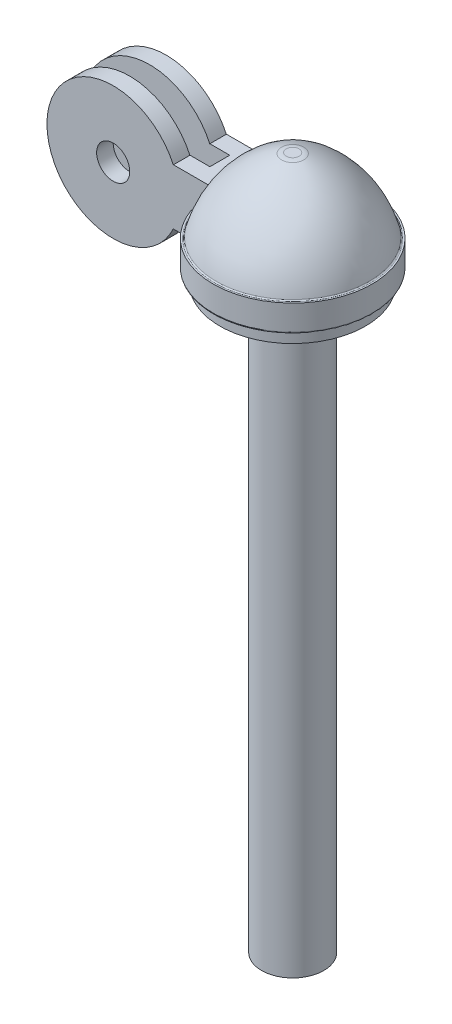
SolidWorks part; units mm, degrees
material "Chrome Stainless Steel"
ref_plane "Front" through (0, 0, 0) normal (0, 0, 1) x (1, 0, 0)
ref_plane "Top" through (0, 0, 0) normal (0, 1, 0) x (1, 0, 0)
ref_plane "Right" through (0, 0, 0) normal (1, 0, 0) x (0, 0, -1)
sketch "Sketch1" plane through (0, 0, 0) normal (0, 0, 1) x (1, 0, 0)
  line L0 (0, 0) -> (0, 19.304) construction
  line L1 (0, 0) -> (15.24, 0)
  line L2 (15.24, 0) -> (15.24, 5.08)
  line L3 (15.24, 5.08) -> (14.732, 5.08)
  line L4 (0, 0) -> (0, 19.304) construction
  line L5 (0, 0) -> (-38.8214, 0) construction
  line L6 (0, 0) -> (0, 19.304) construction
  line L7 (0, 19.304) -> (1.232, 19.304)
  line L8 (0, 0) -> (0, 19.304)
  arc A3 (14.732, 5.08) -> (2.127, 19.1411) centre (-5.08, 0) ccw
  arc A4 (2.127, 19.1411) -> (1.232, 19.304) centre (1.232, 16.764) ccw
  dimension "D5" = 19.304
  dimension "D4" = 0.508
  dimension "D1" = 2.54
  dimension "D6" = 20.4529
  dimension "D2" = 15.24
  dimension "D3" = 5.08
revolve "Revolve4" add sketch "Sketch1" angle 360 about L6
fillet "Fillet2" radius 0.254 2 edges at (0, 0, -15.24) (0, 5.08, -14.732)
sketch "Sketch4" plane through (0, 0, 0) normal (0, -1, 0) x (1, 0, 0)
  circle A0 centre (0, 0) radius 13.97
  dimension "D1" = 27.94
extrude "Boss-Extrude1" add sketch "Sketch4" along normal blind 2.54
sketch "Sketch6" plane through (0, -2.54, 0) normal (0, -1, 0) x (1, 0, 0)
  circle A0 centre (0, 0) radius 5.969
  dimension "D1" = 11.938
extrude "Boss-Extrude2" add sketch "Sketch6" along normal blind 110.998
ref_plane "Plane1" through (-10.16, 0, 0) normal (1, 0, 0) x (0, 0, -1)
sketch "Sketch12" plane through (-10.16, 0, 0) normal (1, 0, 0) x (0, 0, -1)
  line L0 (0, -24.6956) -> (0, 24.849) construction
  line L1 (-5.08, 0.254) -> (5.08, 0.254)
  line L2 (15.24, 0.254) -> (-15.24, 0.254) construction
  line L3 (-5.08, 10.922) -> (5.08, 10.922)
  line L4 (5.08, 10.922) -> (5.08, 0.254)
  line L5 (-5.08, 10.922) -> (-5.08, 0.254)
  point P7 (0, 0.254)
  dimension "D1" = 10.16
  dimension "D2" = 10.668
extrude "Boss-Extrude4" add sketch "Sketch12" against normal blind 7.62
sketch "Sketch13" plane through (-17.78, 0, 0) normal (-1, 0, 0) x (0, 0, 1)
  line L0 (5.08, 10.922) -> (-5.08, 10.922) construction
  line L1 (-1.905, 10.922) -> (1.905, 10.922)
  line L2 (-1.905, 10.922) -> (-1.905, 0.254)
  line L3 (-1.905, 0.254) -> (1.905, 0.254)
  line L4 (1.905, 10.922) -> (1.905, 0.254)
  line L5 (-5.08, 0.254) -> (5.08, 0.254) construction
  line L9 (-5.08, 10.922) -> (-5.08, 5.2686) construction
  dimension "D1" = 3.81
  dimension "D2" = 3.175
extrude "Cut-Extrude1" cut sketch "Sketch13" against normal blind 3.81
ref_plane "Plane2" through (0, 0, 1.905) normal (0, 0, -1) x (-1, 0, 0)
sketch "Sketch14" plane through (0, 0, 1.905) normal (0, 0, -1) x (-1, 0, 0)
  line L0 (17.78, 5.588) -> (29.337, 5.588) construction
  line L1 (17.78, 0.254) -> (17.78, 10.922) construction
  line L2 (17.78, 10.8535) -> (17.78, 0.3225)
  arc A0 (17.78, 0.3225) -> (17.78, 10.8535) centre (29.337, 5.588) ccw
  dimension "D2" = 12.7
  dimension "D1" = 11.557
extrude "Boss-Extrude5" add sketch "Sketch14" against normal blind 3.175
ref_plane "Plane3" through (0, 0, -1.905) normal (0, 0, 1) x (1, 0, 0)
sketch "Sketch16" plane through (0, 0, -1.905) normal (0, 0, 1) x (1, 0, 0)
  line L0 (-17.78, 5.588) -> (-29.337, 5.588) construction
  line L1 (-17.78, 0.254) -> (-17.78, 10.922) construction
  line L2 (-17.78, 10.8535) -> (-17.78, 0.3225)
  arc A0 (-17.78, 10.8535) -> (-17.78, 0.3225) centre (-29.337, 5.588) ccw
  dimension "D1" = 11.557
extrude "Boss-Extrude6" add sketch "Sketch16" against normal blind 3.175
sketch "Sketch17" plane through (0, 0, -5.08) normal (0, 0, -1) x (-1, 0, 0)
  line L0 (42.037, 5.588) -> (29.337, 5.588) construction
  line L1 (29.337, 5.588) -> (29.337, 18.288) construction
  arc A0 (17.78, 0.3225) -> (17.78, 10.8535) centre (29.337, 5.588) ccw construction
sketch "Sketch18" plane through (0, 0, -5.08) normal (0, 0, -1) x (-1, 0, 0)
  circle A0 centre (29.337, 5.588) radius 3.175
  dimension "D1" = 6.35
extrude "Cut-Extrude2" cut sketch "Sketch18" against normal through all
sketch "Sketch19" plane through (0, -113.538, 0) normal (0, -1, 0) x (1, 0, 0)
  circle A0 centre (0, 0) radius 4.7625
  dimension "D1" = 9.525
extrude "Cut-Extrude3" cut sketch "Sketch19" against normal blind 0.254
